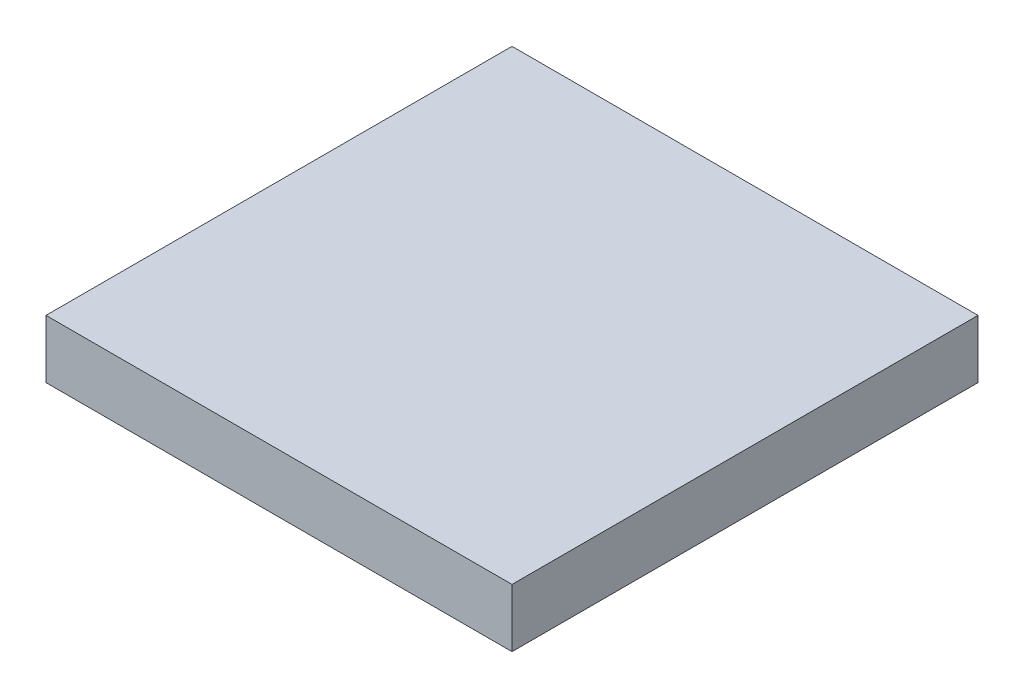
SolidWorks part; units mm, degrees
ref_plane "Front Plane" through (0, 0, 0) normal (0, 0, 1) x (1, 0, 0)
ref_plane "Top Plane" through (0, 0, 0) normal (0, 1, 0) x (1, 0, 0)
ref_plane "Right Plane" through (0, 0, 0) normal (1, 0, 0) x (0, 0, -1)
sketch "Sketch1" plane through (0, 0, 0) normal (0, 1, 0) x (1, 0, 0)
  line L1 (0, 0) -> (12.7, 0)
  line L2 (0, 0) -> (0, 12.7)
  line L3 (0, 12.7) -> (12.7, 12.7)
  line L4 (12.7, 0) -> (12.7, 12.7)
  dimension "D1" = 12.7
  dimension "D2" = 12.7
extrude "Boss-Extrude1" add sketch "Sketch1" along normal blind 1.5875
